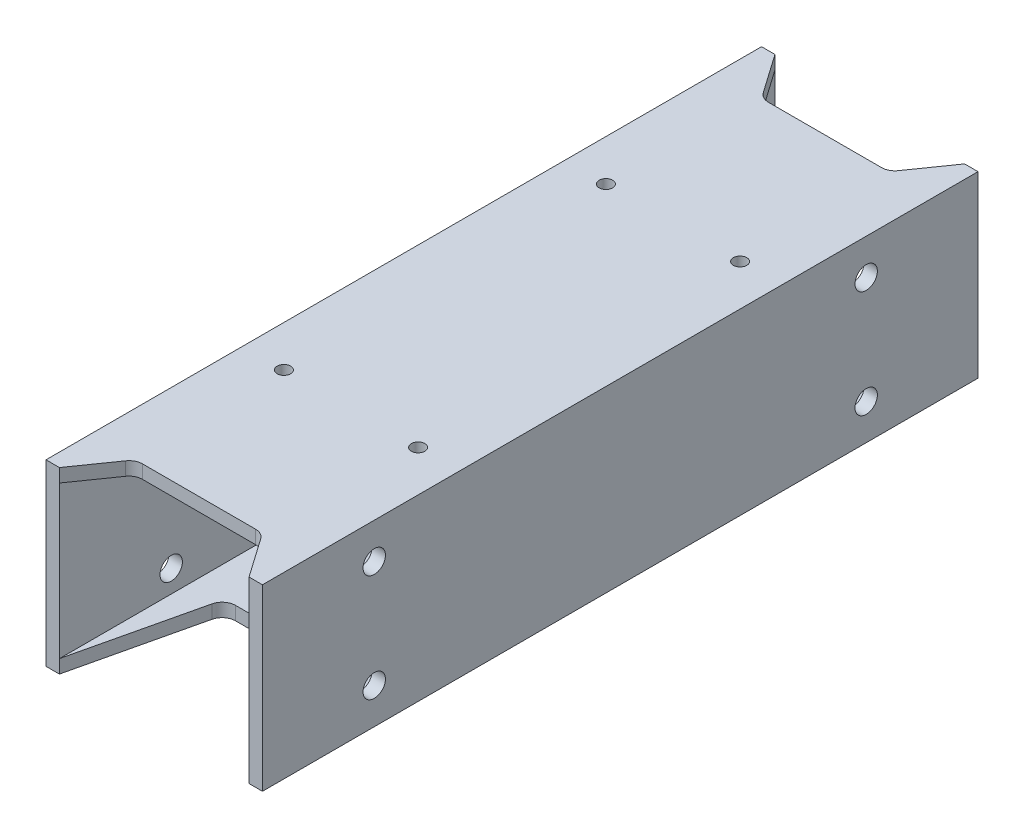
SolidWorks part; units mm, degrees
material "7075-O (SS)"
ref_plane "前视基准面" through (0, 0, 0) normal (0, 0, 1) x (1, 0, 0)
ref_plane "上视基准面" through (0, 0, 0) normal (0, 1, 0) x (1, 0, 0)
ref_plane "右视基准面" through (0, 0, 0) normal (1, 0, 0) x (0, 0, -1)
sketch "草图1" plane through (0, 0, 0) normal (0, 0, 1) x (1, 0, 0)
  line L1 (-24.2, -20) -> (24.2, -20)
  line L2 (-24.2, -20) -> (-24.2, 20)
  line L3 (-24.2, 20) -> (24.2, 20)
  line L4 (24.2, -20) -> (24.2, 20)
  line L5 (-24.2, -20) -> (24.2, 20) construction
  line L6 (-24.2, 20) -> (24.2, -20) construction
  line L7 (-21.2, -17) -> (21.2, -17)
  line L8 (-21.2, -17) -> (-21.2, 17)
  line L9 (-21.2, 17) -> (21.2, 17)
  line L10 (21.2, -17) -> (21.2, 17)
  line L11 (-21.2, -17) -> (21.2, 17) construction
  line L12 (-21.2, 17) -> (21.2, -17) construction
  point P0 (0, 0)
  point P5 (0, 0)
  dimension "D1" = 40
  dimension "D2" = 48.4
  dimension "D3" = 34
  dimension "D4" = 42.4
extrude "凸台-拉伸1" add sketch "草图1" along normal blind 160
sketch "草图2" plane through (24.2, 0, 0) normal (1, 0, 0) x (0, 0, -1)
  line L0 (-80, 20) -> (-80, -20) construction
  line L1 (-160, 20) -> (0, 20) construction
  line L2 (-160, -20) -> (0, -20) construction
  line L4 (-135, -12) -> (-25, -12) construction
  line L5 (-135, -12) -> (-135, 12) construction
  line L6 (-135, 12) -> (-25, 12) construction
  line L7 (-25, -12) -> (-25, 12) construction
  line L8 (-135, -12) -> (-25, 12) construction
  line L9 (-135, 12) -> (-25, -12) construction
  circle A0 centre (-135, 12) radius 2.5
  circle A1 centre (-135, -12) radius 2.5
  circle A2 centre (-25, 12) radius 2.5
  circle A3 centre (-25, -12) radius 2.5
  point P14 (-80, 0)
  dimension "D3" = 5
  dimension "D4" = 5
  dimension "D5" = 5
  dimension "D6" = 5
  dimension "D1" = 24
  dimension "D2" = 110
extrude "切除-拉伸1" cut sketch "草图2" against normal blind 18
sketch "草图4" plane through (-24.2, 0, 0) normal (-1, 0, 0) x (0, 0, 1)
  line L0 (80, 20) -> (80, -20) construction
  line L1 (160, 20) -> (0, 20) construction
  line L2 (160, -20) -> (0, -20) construction
  line L4 (25, -12) -> (135, -12) construction
  line L5 (25, -12) -> (25, 12) construction
  line L6 (25, 12) -> (135, 12) construction
  line L7 (135, -12) -> (135, 12) construction
  line L8 (25, -12) -> (135, 12) construction
  line L9 (25, 12) -> (135, -12) construction
  circle A0 centre (25, 12) radius 2.5
  circle A1 centre (25, -12) radius 2.5
  circle A2 centre (135, 12) radius 2.5
  circle A3 centre (135, -12) radius 2.5
  point P6 (80, 0)
  dimension "D3" = 5
  dimension "D4" = 5
  dimension "D5" = 5
  dimension "D6" = 5
  dimension "D1" = 24
  dimension "D2" = 110
extrude "切除-拉伸3" cut sketch "草图4" against normal blind 10
sketch "草图6" plane through (0, 20, 0) normal (0, 1, 0) x (1, 0, 0)
  line L1 (19.2, -120) -> (14.2, -85)
  line L2 (-19.2, -40) -> (19.2, -40)
  line L4 (-14.2, -75) -> (14.2, -75)
  line L7 (-24.2, -80) -> (24.2, -80) construction
  line L8 (-24.2, -160) -> (-24.2, 0) construction
  line L9 (24.2, -160) -> (24.2, 0) construction
  line L13 (-19.2, -120) -> (19.2, -120)
  line L14 (-19.2, -120) -> (-14.2, -85)
  line L15 (-19.2, -40) -> (-14.2, -75)
  line L16 (-14.2, -85) -> (14.2, -85)
  line L17 (19.2, -40) -> (14.2, -75)
  line L18 (-19.2, -120) -> (19.2, -120)
sketch "草图8" plane through (0, 20, 0) normal (0, 1, 0) x (1, 0, 0)
  line L0 (0, 0) -> (0, -160) construction
  line L1 (24.2, -160) -> (-24.2, -160) construction
  line L3 (-15, -116) -> (15, -116) construction
  line L4 (-15, -116) -> (-15, -44) construction
  line L5 (-15, -44) -> (15, -44) construction
  line L6 (15, -116) -> (15, -44) construction
  line L7 (-15, -116) -> (15, -44) construction
  line L8 (-15, -44) -> (15, -116) construction
  circle A0 centre (-15, -44) radius 1.5
  circle A1 centre (15, -44) radius 1.5
  circle A2 centre (-15, -116) radius 1.5
  circle A3 centre (15, -116) radius 1.5
  point P5 (0, -80)
  dimension "D3" = 3
  dimension "D4" = 3
  dimension "D5" = 3
  dimension "D6" = 3
  dimension "D1" = 72
  dimension "D2" = 30
extrude "切除-拉伸6" cut sketch "草图8" against normal blind 50
sketch "草图9" plane through (0, -20, 0) normal (0, -1, 0) x (1, 0, 0)
  line L0 (-24.2, 80) -> (24.2, 80) construction
  line L1 (-24.2, 160) -> (24.2, 160) construction
  line L2 (-21.2, 160) -> (21.2, 160) construction
  line L3 (21.2, 160) -> (21.2, 130) construction
  line L4 (21.2, 130) -> (14.2, 130) construction
  line L5 (14.2, 130) -> (-14.2, 130) construction
  line L6 (-21.2, 160) -> (-14.2, 130)
  line L7 (-14.2, 130) -> (14.2, 130)
  line L8 (14.2, 130) -> (21.2, 160)
  line L9 (21.2, 160) -> (-21.2, 160)
  line L10 (-24.2, 160) -> (-24.2, 0) construction
  line L11 (24.2, 160) -> (24.2, 0) construction
  line L12 (14.2, 30) -> (-14.2, 30) construction
  line L13 (21.2, 30) -> (14.2, 30) construction
  line L14 (21.2, 0) -> (21.2, 30) construction
  line L15 (-21.2, 0) -> (21.2, 0) construction
  line L16 (21.2, 0) -> (-21.2, 0)
  line L17 (14.2, 30) -> (21.2, 0)
  line L18 (-14.2, 30) -> (14.2, 30)
  line L19 (-21.2, 0) -> (-14.2, 30)
  dimension "D2" = 42.4
  dimension "D3" = 30
  dimension "D4" = 7
  dimension "D5" = 28.4
extrude "切除-拉伸7" cut sketch "草图9" against normal blind 10
fillet "圆角1" radius 3 4 edges at (-14.2, -18.5, 30) (14.2, -18.5, 30) (14.2, -18.5, 130) (-14.2, -18.5, 130)
sketch "草图10" plane through (0, 20, 0) normal (0, 1, 0) x (1, 0, 0)
  line L0 (-24.2, 0) -> (-21.2, 0) construction
  line L1 (24.2, 0) -> (-24.2, 0) construction
  line L2 (-21.2, 0) -> (-21.2, -10) construction
  line L3 (-21.2, -10) -> (21.2, -10) construction
  line L4 (21.2, -10) -> (21.2, 0) construction
  line L5 (-21.2, -10) -> (-14.2, -10) construction
  line L6 (-21.2, 0) -> (-14.2, -10)
  line L7 (-14.2, -10) -> (14.2, -10)
  line L8 (14.2, -10) -> (21.2, 0)
  line L9 (21.2, 0) -> (-21.2, 0)
  line L10 (-24.2, -80) -> (24.2, -80) construction
  line L11 (-24.2, -160) -> (-24.2, 0) construction
  line L12 (24.2, -160) -> (24.2, 0) construction
  line L13 (-21.2, -150) -> (-14.2, -150) construction
  line L14 (21.2, -150) -> (21.2, -160) construction
  line L15 (-21.2, -150) -> (21.2, -150) construction
  line L16 (-21.2, -160) -> (-21.2, -150) construction
  line L17 (-24.2, -160) -> (-21.2, -160) construction
  line L18 (21.2, -160) -> (-21.2, -160)
  line L19 (14.2, -150) -> (21.2, -160)
  line L20 (-14.2, -150) -> (14.2, -150)
  line L21 (-21.2, -160) -> (-14.2, -150)
  dimension "D1" = 3
  dimension "D2" = 10
  dimension "D3" = 42.4
  dimension "D4" = 7
  dimension "D5" = 28.4
extrude "切除-拉伸8" cut sketch "草图10" against normal blind 10 contours L9 L6 L7 L8 | L18 L21 L20 L19
fillet "圆角2" radius 3 4 edges at (-14.2, 18.5, 150) (14.2, 18.5, 150) (-14.2, 18.5, 10) (14.2, 18.5, 10)
